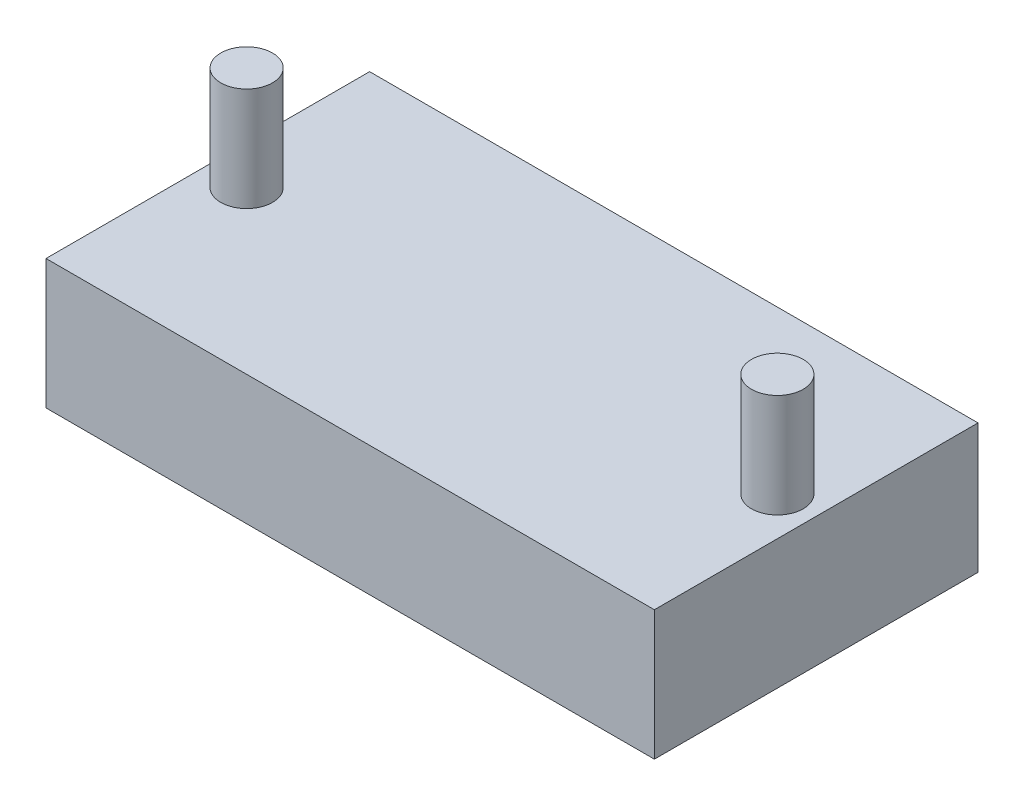
SolidWorks part; units mm, degrees
ref_plane "Front Plane" through (0, 0, 0) normal (0, 0, 1) x (1, 0, 0)
ref_plane "Top Plane" through (0, 0, 0) normal (0, 1, 0) x (1, 0, 0)
ref_plane "Right Plane" through (0, 0, 0) normal (1, 0, 0) x (0, 0, -1)
sketch "Sketch1" plane through (0, 0, 0) normal (0, 1, 0) x (1, 0, 0)
  line L1 (0, 0) -> (47, 0)
  line L2 (0, 0) -> (0, 25)
  line L3 (0, 25) -> (47, 25)
  line L4 (47, 0) -> (47, 25)
  dimension "D1" = 25
  dimension "D2" = 47
extrude "Boss-Extrude1" add sketch "Sketch1" along normal blind 10
sketch "Sketch2" plane through (0, 10, 0) normal (0, 1, 0) x (1, 0, 0)
  line L0 (0, 12.5) -> (3, 12.5) construction
  line L1 (0, 25) -> (0, 0) construction
  line L2 (23.5, 25) -> (23.5, 0) construction
  line L3 (47, 25) -> (0, 25) construction
  line L4 (0, 0) -> (47, 0) construction
  circle A0 centre (3, 12.5) radius 2
  circle A1 centre (44, 12.5) radius 2
  dimension "D2" = 4
  dimension "D1" = 3
extrude "Boss-Extrude2" add sketch "Sketch2" along normal blind 8
